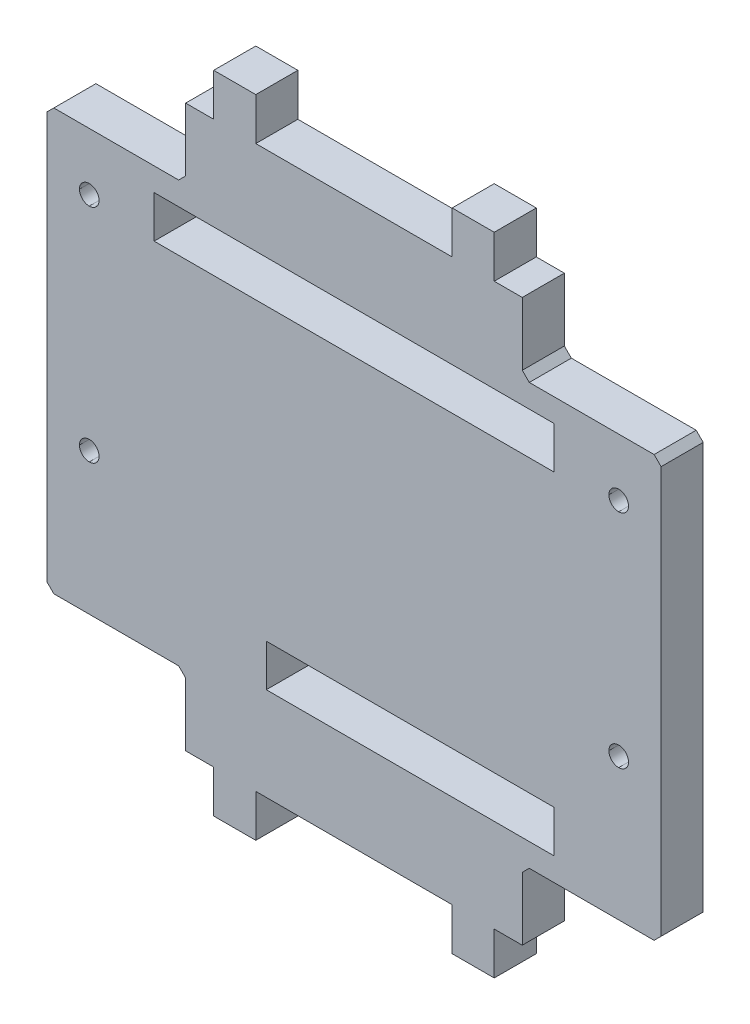
SolidWorks part; units mm, degrees
ref_plane "Alzado" through (0, 0, 0) normal (0, 0, 1) x (1, 0, 0)
ref_plane "Planta" through (0, 0, 0) normal (0, 1, 0) x (1, 0, 0)
ref_plane "Vista lateral" through (0, 0, 0) normal (1, 0, 0) x (0, 0, -1)
sketch "Corte" plane through (0, 0, 0) normal (0, 0, 1) x (1, 0, 0)
  line L0 (113.9999, 146.05) -> (113.9999, 140)
  line L1 (80, 53.95) -> (86, 53.95)
  line L2 (119.9999, 146.05) -> (119.9999, 140)
  line L3 (86, 146.05) -> (86, 140)
  line L4 (80, 146.05) -> (80, 140)
  line L5 (76, 60) -> (80, 60)
  line L6 (76, 140) -> (80, 140)
  line L7 (80, 146.05) -> (86, 146.05)
  line L8 (57.2001, 130) -> (75, 130)
  line L9 (57.2001, 70) -> (75, 70)
  line L10 (143.8001, 71) -> (143.8001, 129)
  line L11 (56.2001, 71) -> (56.2001, 129)
  line L12 (123.9999, 140) -> (123.9999, 131)
  line L13 (76, 140) -> (76, 131)
  line L14 (86, 140) -> (113.9999, 140)
  line L15 (113.9999, 146.05) -> (119.9999, 146.05)
  line L16 (119.9999, 140) -> (123.9999, 140)
  line L17 (114, 53.95) -> (120, 53.95)
  line L18 (120, 60) -> (124, 60)
  line L19 (120, 60) -> (120, 53.95)
  line L20 (114, 60) -> (114, 53.95)
  line L21 (86, 60) -> (86, 53.95)
  line L22 (80, 60) -> (80, 53.95)
  line L23 (124.9999, 130) -> (142.8001, 130)
  line L24 (124, 69) -> (124, 60)
  line L25 (125, 70) -> (142.8001, 70)
  line L26 (76, 69) -> (76, 60)
  line L27 (71.5001, 126.7) -> (128.5001, 126.7)
  line L28 (87.5001, 73.3) -> (128.5001, 73.3)
  line L29 (87.5001, 73.3) -> (87.5001, 79.3)
  line L30 (128.5001, 73.3) -> (128.5001, 79.3)
  line L31 (87.5001, 79.3) -> (128.5001, 79.3)
  line L32 (71.5001, 120.7) -> (128.5001, 120.7)
  line L33 (71.5001, 120.7) -> (71.5001, 126.7)
  line L34 (128.5001, 120.7) -> (128.5001, 126.7)
  line L35 (86, 60) -> (114, 60)
  line L36 (143.8001, 129) -> (142.8001, 130)
  line L37 (143.8001, 71) -> (142.8001, 70)
  line L38 (125, 70) -> (124, 69)
  line L39 (75, 70) -> (76, 69)
  line L40 (56.2001, 71) -> (57.2001, 70)
  line L41 (56.2001, 129) -> (57.2001, 130)
  line L42 (75, 130) -> (76, 131)
  line L43 (123.9999, 131) -> (124.9999, 130)
  spline S0 degree 3 poles (139.1471, 90.2) (139.1471, 89.4285) (138.5216, 88.803) (137.7501, 88.803) knots 0 0 0 0 1 1 1 1
  spline S1 degree 3 poles (137.7501, 88.803) (136.9785, 88.803) (136.3531, 89.4285) (136.3531, 90.2) knots 0 0 0 0 1 1 1 1
  spline S2 degree 3 poles (136.3531, 90.2) (136.3531, 90.9715) (136.9785, 91.597) (137.7501, 91.597) knots 0 0 0 0 1 1 1 1
  spline S3 degree 3 poles (137.7501, 91.597) (138.5216, 91.597) (139.1471, 90.9715) (139.1471, 90.2) knots 0 0 0 0 1 1 1 1
  spline S4 degree 3 poles (139.1471, 121.8) (139.1471, 121.0285) (138.5216, 120.403) (137.7501, 120.403) knots 0 0 0 0 1 1 1 1
  spline S5 degree 3 poles (137.7501, 120.403) (136.9785, 120.403) (136.3531, 121.0285) (136.3531, 121.8) knots 0 0 0 0 1 1 1 1
  spline S6 degree 3 poles (136.3531, 121.8) (136.3531, 122.5715) (136.9785, 123.197) (137.7501, 123.197) knots 0 0 0 0 1 1 1 1
  spline S7 degree 3 poles (137.7501, 123.197) (138.5216, 123.197) (139.1471, 122.5715) (139.1471, 121.8) knots 0 0 0 0 1 1 1 1
  spline S8 degree 3 poles (63.6471, 121.8) (63.6471, 121.0285) (63.0216, 120.403) (62.2501, 120.403) knots 0 0 0 0 1 1 1 1
  spline S9 degree 3 poles (62.2501, 120.403) (61.4785, 120.403) (60.8531, 121.0285) (60.8531, 121.8) knots 0 0 0 0 1 1 1 1
  spline S10 degree 3 poles (60.8531, 121.8) (60.8531, 122.5715) (61.4785, 123.197) (62.2501, 123.197) knots 0 0 0 0 1 1 1 1
  spline S11 degree 3 poles (62.2501, 123.197) (63.0216, 123.197) (63.6471, 122.5715) (63.6471, 121.8) knots 0 0 0 0 1 1 1 1
  spline S12 degree 3 poles (63.6471, 90.2) (63.6471, 89.4285) (63.0216, 88.803) (62.2501, 88.803) knots 0 0 0 0 1 1 1 1
  spline S13 degree 3 poles (62.2501, 88.803) (61.4785, 88.803) (60.8531, 89.4285) (60.8531, 90.2) knots 0 0 0 0 1 1 1 1
  spline S14 degree 3 poles (60.8531, 90.2) (60.8531, 90.9715) (61.4785, 91.597) (62.2501, 91.597) knots 0 0 0 0 1 1 1 1
  spline S15 degree 3 poles (62.2501, 91.597) (63.0216, 91.597) (63.6471, 90.9715) (63.6471, 90.2) knots 0 0 0 0 1 1 1 1
sketch "Grabado" plane through (0, 0, 0) normal (0, 0, 1) x (1, 0, 0)
  line L0 (59.5001, 72.3) -> (140.5001, 72.3)
  line L1 (58.5001, 73.3) -> (58.5001, 126.7)
  line L2 (141.5001, 73.3) -> (141.5001, 126.7)
  line L3 (59.5001, 127.7) -> (140.5001, 127.7)
  line L4 (58.5001, 73.3) -> (59.5001, 72.3)
  line L5 (140.5001, 72.3) -> (141.5001, 73.3)
  line L6 (141.5001, 126.7) -> (140.5001, 127.7)
  line L7 (59.5001, 127.7) -> (58.5001, 126.7)
extrude "Saliente-Extruir1" add sketch "Corte" against normal blind 6
